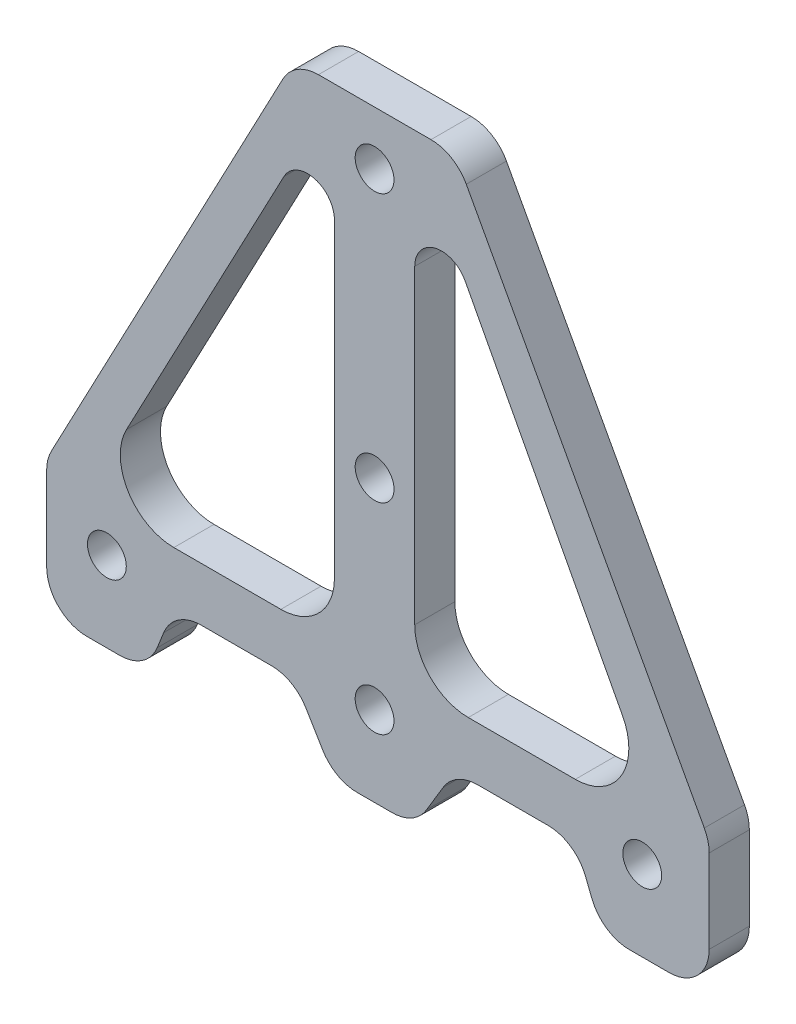
SolidWorks part; units mm, degrees
material "Thornel Mat VMA"
ref_plane "前视基准面" through (0, 0, 0) normal (0, 0, 1) x (1, 0, 0)
ref_plane "上视基准面" through (0, 0, 0) normal (0, 1, 0) x (1, 0, 0)
ref_plane "右视基准面" through (0, 0, 0) normal (1, 0, 0) x (0, 0, -1)
sketch "草图1" plane through (0, 0, 0) normal (0, 0, 1) x (1, 0, 0)
  line L0 (20, 0) -> (-20, 0) construction
  line L1 (0, 0) -> (0, 35) construction
  line L2 (-24.5, -6) -> (25, -6)
  line L3 (25, -6) -> (25, 4)
  line L4 (25, 4) -> (6, 39)
  line L5 (6, 39) -> (-6, 39)
  line L6 (-6, 39) -> (-24.5, 4)
  line L7 (-24.5, 4) -> (-24.5, -6)
  line L8 (-3, 30.1923) -> (-3, 3)
  line L9 (-3, 3) -> (-21.6353, 3)
  line L10 (-21.6353, 3) -> (-6.7682, 31.1269)
  line L11 (21.6353, 3) -> (6.7682, 31.1269)
  line L12 (3, 3) -> (21.6353, 3)
  line L13 (3, 30.1923) -> (3, 3)
  circle A0 centre (-20, 0) radius 1.45
  circle A1 centre (20, 0) radius 1.45
  circle A2 centre (0, 35) radius 1.45
  circle A3 centre (0, 15) radius 1.45
  circle A4 centre (0, 0) radius 1.45
  arc A5 (-3, 30.1923) -> (-6.7682, 31.1269) centre (-5, 30.1923) ccw
  arc A6 (3, 30.1923) -> (6.7682, 31.1269) centre (5, 30.1923) cw
  point P4 (0, 0)
  dimension "D3" = 2.9
  dimension "D16" = 2
  dimension "D1" = 40
  dimension "D2" = 35
  dimension "D4" = 20
  dimension "D5" = 6
  dimension "D6" = 4
  dimension "D7" = 4
  dimension "D8" = 6
  dimension "D9" = 6
  dimension "D10" = 4
  dimension "D11" = 4.5
  dimension "D12" = 5
  dimension "D13" = 3
  dimension "D14" = 3
  dimension "D15" = 3
extrude "凸台-拉伸1" add sketch "草图1" along normal blind 3
sketch "草图3" plane through (0, 0, 3) normal (0, 0, 1) x (1, 0, 0)
  line L0 (-17, -6) -> (-15, -1)
  line L1 (-24.5, -6) -> (25, -6) construction
  line L2 (-15, -1) -> (-6, -1)
  line L3 (-6, -1) -> (-3, -6)
  line L4 (-3, -6) -> (-17, -6)
  line L5 (-21.6353, 3) -> (-3, 3) construction
  line L6 (0, -1000) -> (0, 49000) construction
  line L7 (3, -6) -> (17, -6)
  line L8 (6, -1) -> (3, -6)
  line L9 (15, -1) -> (6, -1)
  line L10 (17, -6) -> (15, -1)
  circle A0 centre (-20, 0) radius 1.45 construction
  dimension "D1" = 6
  dimension "D2" = 3
  dimension "D3" = 5
  dimension "D4" = 3
  dimension "D5" = 4
extrude "切除-拉伸1" cut sketch "草图3" against normal blind 3
fillet "圆角1" radius 3 14 edges at (-17, -6, 1.5) (-24.5, -6, 1.5) (-6, 39, 1.5) (6, 39, 1.5) (25, 4, 1.5) (25, -6, 1.5) (17, -6, 1.5) (15, -1, 1.5) (6, -1, 1.5) (3, -6, 1.5) (-3, -6, 1.5) (-6, -1, 1.5) (-15, -1, 1.5) (-24.5, 4, 1.5)
fillet "圆角2" radius 4 4 edges at (3, 3, 1.5) (21.6353, 3, 1.5) (-3, 3, 1.5) (-21.6353, 3, 1.5)
